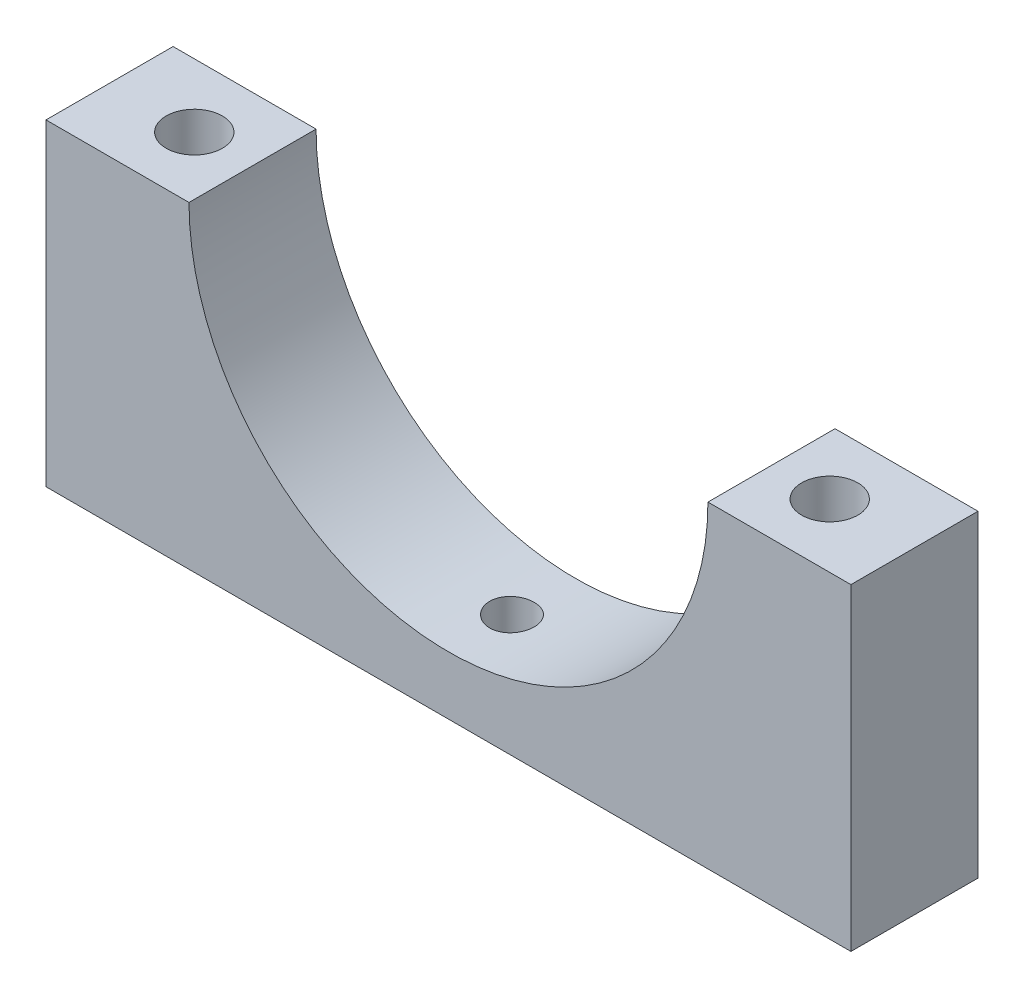
SolidWorks part; units mm, degrees
ref_plane "前视基准面" through (0, 0, 0) normal (0, 0, 1) x (1, 0, 0)
ref_plane "上视基准面" through (0, 0, 0) normal (0, 1, 0) x (1, 0, 0)
ref_plane "右视基准面" through (0, 0, 0) normal (1, 0, 0) x (0, 0, -1)
sketch "草图1" plane through (0, 0, 0) normal (0, 1, 0) x (1, 0, 0)
  line L0 (0, 0) -> (20.1906, 0) construction
  line L1 (0, 0) -> (0, 23.0129) construction
  line L3 (-38, 6) -> (38, 6)
  line L4 (-38, 6) -> (-38, -6)
  line L5 (-38, -6) -> (38, -6)
  line L6 (38, 6) -> (38, -6)
  dimension "D1" = 76
  dimension "D2" = 12
extrude "凸台-拉伸1" add sketch "草图1" against normal blind 30
sketch "草图2" plane through (0, 0, 6) normal (0, 0, 1) x (1, 0, 0)
  circle A0 centre (0, 0) radius 24.5
  dimension "D1" = 49
extrude "切除-拉伸1" cut sketch "草图2" against normal up to next
hole_wizard "M5 螺纹孔1" positions "草图4" profile "草图3" tap size "M5" standard "GB" end condition up to next
sketch "草图4" plane through (0, -30, 0) normal (0, -1, 0) x (1, 0, 0)
  point P0 (0, 0)
sketch "草图3" plane through (0, -30, 0) normal (1, 0, 0) x (0, 0, -1)
  line L0 (0, 0) -> (0, 5.5)
  line L1 (0, 5.5) -> (2.1, 5.5)
  line L2 (2.1, 5.5) -> (2.1, 0)
  line L5 (2.1, 0) -> (0, 0)
  line L11 (0, -6.35) -> (0, 13.021) construction
  dimension "通孔螺纹孔钻头直径" = 4.2
  dimension "通孔螺纹孔钻头深度" = 5.5
cosmetic thread "孔螺蚊线2" parameters "D1"=5.5902, "D2"=5
hole_wizard "打孔尺寸根据内六角圆柱头螺钉的类型1" positions "草图6" profile "草图5" counterbore size "M5" standard "GB" end condition through all
sketch "草图6" plane through (0, -30, 0) normal (0, -1, 0) x (1, 0, 0)
  line L0 (0, 0) -> (0, 9.576) construction
  line L1 (0, 0) -> (9.4287, 0) construction
  point P0 (-30, 0)
  point P11 (30, 0)
  dimension "D1" = 60
sketch "草图5" plane through (-30, -30, 0) normal (1, 0, 0) x (0, 0, -1)
  line L0 (0, 0) -> (0, 30)
  line L1 (0, 30) -> (2.65, 30)
  line L3 (2.65, 30) -> (2.65, 8.7)
  line L4 (2.65, 8.7) -> (5, 8.7)
  line L5 (5, 8.7) -> (5, 0)
  line L7 (5, 0) -> (0, 0)
  line L11 (0, -6.35) -> (0, 107.95) construction
  dimension "通孔孔直径" = 5.3
  dimension "通孔孔深度" = 30
  dimension "柱形沉头孔直径" = 10
  dimension "柱形沉头孔深度" = 8.7
